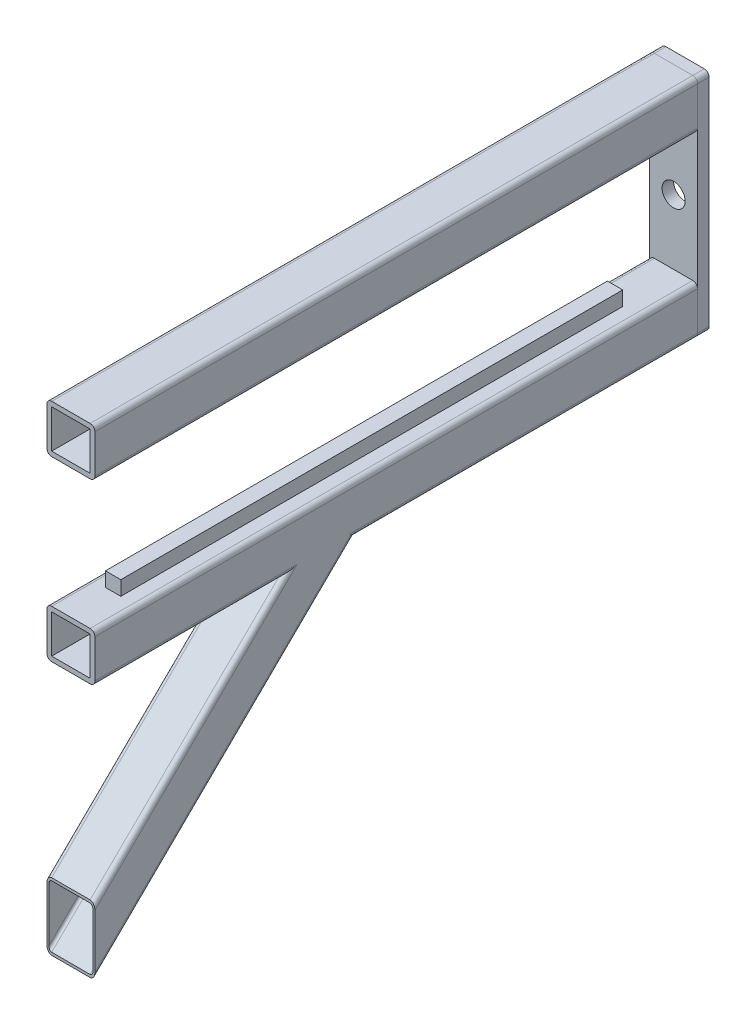
SolidWorks part; units mm, degrees
ref_plane "Front Plane" through (0, 0, 0) normal (0, 0, 1) x (1, 0, 0)
ref_plane "Top Plane" through (0, 0, 0) normal (0, 1, 0) x (1, 0, 0)
ref_plane "Right Plane" through (0, 0, 0) normal (1, 0, 0) x (0, 0, -1)
sketch "Sketch1" plane through (0, 0, 0) normal (0, 0, 1) x (1, 0, 0)
  line L0 (-20, 20) -> (20, 20)
  line L1 (-20, -25) -> (20, -25)
  line L2 (-25, -20) -> (-25, 20)
  line L3 (-20, 25) -> (20, 25)
  line L4 (25, -20) -> (25, 20)
  line L5 (-25, -25) -> (25, 25) construction
  line L6 (-25, 25) -> (25, -25) construction
  line L7 (20, -20) -> (20, 20)
  line L8 (-20, -20) -> (20, -20)
  line L9 (-20, -20) -> (-20, 20)
  line L10 (-25, -25) -> (25, -25) construction
  line L11 (25, -25) -> (25, 25) construction
  line L12 (-25, -25) -> (-25, 25) construction
  line L13 (-25, 25) -> (25, 25) construction
  line L14 (-20, -165) -> (20, -165)
  line L15 (-20, -210) -> (20, -210)
  line L16 (-25, -205) -> (-25, -165)
  line L17 (-20, -160) -> (20, -160)
  line L18 (25, -205) -> (25, -165)
  line L19 (20, -205) -> (20, -165)
  line L20 (-20, -205) -> (20, -205)
  line L21 (-20, -205) -> (-20, -165)
  line L22 (-25, -210) -> (25, -160) construction
  line L23 (-25, -160) -> (25, -210) construction
  arc A0 (20, -25) -> (25, -20) centre (20, -20) ccw
  arc A1 (-20, -25) -> (-25, -20) centre (-20, -20) cw
  arc A2 (20, 25) -> (25, 20) centre (20, 20) cw
  arc A3 (-25, 20) -> (-20, 25) centre (-20, 20) cw
  arc A4 (20, -210) -> (25, -205) centre (20, -205) ccw
  arc A5 (-20, -210) -> (-25, -205) centre (-20, -205) cw
  arc A6 (20, -160) -> (25, -165) centre (20, -165) cw
  arc A7 (-25, -165) -> (-20, -160) centre (-20, -165) cw
  point P0 (0, 0)
  point P24 (0, -185)
  dimension "D3" = 5
  dimension "D1" = 50
  dimension "D2" = 5
  dimension "D5" = 235
  dimension "D4" = 2
extrude "Boss-Extrude1" add sketch "Sketch1" along normal blind 628
sketch "Sketch2" plane through (0, 0, 0) normal (0, 0, 1) x (1, 0, 0)
  line L0 (25, -205) -> (25, -165) construction
  line L2 (-25, -165) -> (-25, -205) construction
  line L3 (-20, -210) -> (20, -210) construction
  line L4 (25, -20) -> (25, 20) construction
  line L5 (20, 25) -> (-20, 25) construction
  line L6 (-25, 20) -> (-25, -20) construction
  line L8 (25, -205) -> (25, -165)
  line L9 (-25, -165) -> (-25, -20)
  line L10 (-25, -165) -> (-25, -205)
  line L11 (-20, -210) -> (20, -210)
  line L12 (25, -20) -> (25, 20)
  line L13 (20, 25) -> (-20, 25)
  line L14 (-25, 20) -> (-25, -20)
  line L15 (25, -20) -> (25, -165)
  line L16 (20, -165) -> (-20, -165) construction
  line L17 (-20, -165) -> (-20, -205) construction
  arc A0 (20, -210) -> (25, -205) centre (20, -205) ccw construction
  arc A3 (-25, -205) -> (-20, -210) centre (-20, -205) ccw construction
  arc A5 (25, 20) -> (20, 25) centre (20, 20) ccw construction
  arc A6 (-20, 25) -> (-25, 20) centre (-20, 20) ccw construction
  arc A8 (20, -210) -> (25, -205) centre (20, -205) ccw
  circle A9 centre (0, 0) radius 6.25
  circle A10 centre (0, -185) radius 6.25
  arc A11 (-25, -205) -> (-20, -210) centre (-20, -205) ccw
  circle A12 centre (0, -92.5) radius 12
  arc A13 (25, 20) -> (20, 25) centre (20, 20) ccw
  arc A14 (-20, 25) -> (-25, 20) centre (-20, 20) ccw
  point P23 (0, -165)
  point P24 (-25, -92.5)
  point P28 (-20, -185)
  dimension "D1" = 12.5
  dimension "D2" = 24
extrude "Boss-Extrude2" add sketch "Sketch2" against normal blind 12 separate body
sketch "Sketch3" plane through (0, 0, 628) normal (0, 0, 1) x (1, 0, 0)
  line L0 (0, -92.5) -> (94.2615, -92.5) construction
  line L1 (-9, -25) -> (-9, -40)
  line L2 (-20, -25) -> (20, -25) construction
  line L3 (-9, -40) -> (7, -40)
  line L4 (7, -40) -> (7, -25)
  line L5 (7, -25) -> (-9, -25)
  line L6 (7, -160) -> (-9, -160)
  line L7 (7, -145) -> (7, -160)
  line L8 (-9, -145) -> (7, -145)
  line L9 (-9, -160) -> (-9, -145)
  line L12 (25, -205) -> (25, 20) construction
  dimension "D1" = 16
  dimension "D2" = 15
  dimension "D3" = 18
extrude "Boss-Extrude4" add sketch "Sketch3" against normal offset from surface (523 mm away) 60 from offset 45 separate body contours L3 L4 L5 L1 | L8 L7 L6 L9 up to face at (12, -92.5, 0) offset against normal yes
sketch "Sketch4" plane through (0, 0, 0) normal (1, 0, 0) x (0, 0, -1)
  line L0 (-711.4129, -556.8682) -> (-358, -210)
  line L1 (-628, -210) -> (0, -210) construction
  line L2 (-628, -205) -> (-628, -165) construction
  line L3 (-628, 25) -> (0, 25) construction
  line L4 (12, -205) -> (12, 20) construction
  point P5 (-628, -475)
  point P8 (-628, -185)
  dimension "D1" = 500
  dimension "D2" = 370
ref_plane "Plane1" through (0, -210, 358) normal (0, 0.7005, -0.7137) x (-1, 0, 0)
sketch "Sketch5" plane through (0, -210, 358) normal (0, 0.7005, -0.7137) x (-1, 0, 0)
  line L0 (20, 2) -> (-20, 2)
  line L1 (20, 0) -> (-20, 0)
  line L2 (25, 5) -> (25, 45)
  line L3 (20, 50) -> (-20, 50)
  line L4 (-25, 5) -> (-25, 45)
  line L5 (-23, 5) -> (-23, 45)
  line L6 (20, 48) -> (-20, 48)
  line L7 (23, 5) -> (23, 45)
  arc A0 (20, 0) -> (25, 5) centre (20, 5) ccw
  arc A1 (25, 45) -> (20, 50) centre (20, 45) ccw
  arc A2 (-20, 0) -> (-25, 5) centre (-20, 5) cw
  arc A3 (-20, 50) -> (-25, 45) centre (-20, 45) ccw
  arc A4 (-20, 2) -> (-23, 5) centre (-20, 5) cw
  arc A5 (-20, 48) -> (-23, 45) centre (-20, 45) ccw
  arc A6 (23, 45) -> (20, 48) centre (20, 45) ccw
  arc A7 (20, 2) -> (23, 5) centre (20, 5) ccw
  point P4 (0, 0)
  point P8 (25, 0)
  point P11 (25, 50)
  dimension "D2" = 5
  dimension "D1" = 50
  dimension "D3" = 2
sweep "Sweep1" add profiles "Sketch5" path "Sketch4"
sketch "Sketch6" plane through (0, 0, 628) normal (0, 0, 1) x (1, 0, 0)
  line L1 (-341.6025, 616.657) -> (341.6025, 616.657)
  line L2 (-341.6025, 616.657) -> (-341.6025, -616.657)
  line L3 (-341.6025, -616.657) -> (341.6025, -616.657)
  line L4 (341.6025, 616.657) -> (341.6025, -616.657)
  line L5 (-341.6025, 616.657) -> (341.6025, -616.657) construction
  line L6 (-341.6025, -616.657) -> (341.6025, 616.657) construction
  point P0 (0, 0)
extrude "Cut-Extrude1" cut sketch "Sketch6" along normal through all
